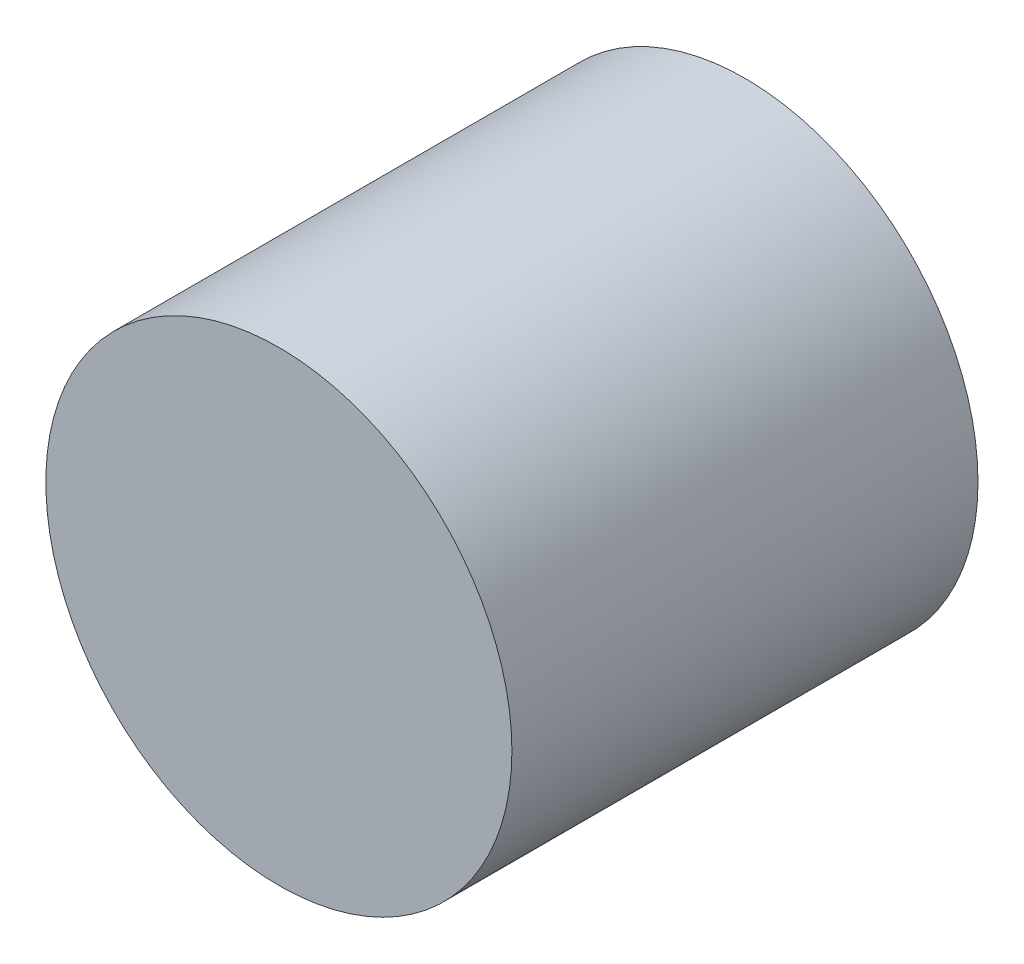
SolidWorks part; units mm, degrees
ref_plane "前视基准面" through (0, 0, 0) normal (0, 0, 1) x (1, 0, 0)
ref_plane "上视基准面" through (0, 0, 0) normal (0, 1, 0) x (1, 0, 0)
ref_plane "右视基准面" through (0, 0, 0) normal (1, 0, 0) x (0, 0, -1)
other "Configuration Table"
sketch "草图1" plane through (0, 0, 0) normal (0, 0, 1) x (1, 0, 0)
  circle A0 centre (0, 0) radius 12
extrude "凸台-拉伸1" add sketch "草图1" against normal blind 24
